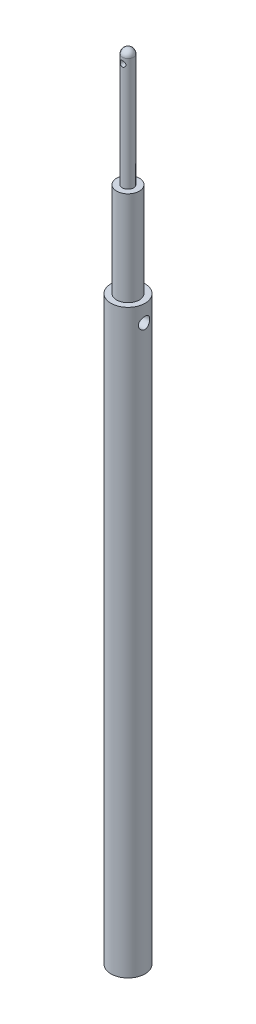
SolidWorks part; units mm, degrees
ref_plane "Front Plane" through (0, 0, 0) normal (0, 0, 1) x (1, 0, 0)
ref_plane "Top Plane" through (0, 0, 0) normal (0, 1, 0) x (1, 0, 0)
ref_plane "Right Plane" through (0, 0, 0) normal (1, 0, 0) x (0, 0, -1)
sketch "Sketch1" plane through (0, 0, 0) normal (0, 1, 0) x (1, 0, 0)
  circle A0 centre (0, 0) radius 9
  dimension "D1" = 18
extrude "Boss-Extrude1" add sketch "Sketch1" along normal blind 308
sketch "Sketch3" plane through (0, 0, 0) normal (1, 0, 0) x (0, 0, -1)
  line L1 (0, -1000) -> (0, 49000) construction
  line L2 (-1000, 299) -> (49000, 299) construction
  line L3 (9, 308) -> (-9, 308) construction
  circle A0 centre (0, 299) radius 3
  dimension "D1" = 6
  dimension "D2" = 9
extrude "Cut-Extrude1" cut sketch "Sketch3" against normal mid plane 200
sketch "Sketch4" plane through (0, 308, 0) normal (0, 1, 0) x (1, 0, 0)
  circle A0 centre (0, 0) radius 6
extrude "Boss-Extrude2" add sketch "Sketch4" along normal blind 50
sketch "Sketch5" plane through (0, 358, 0) normal (0, 1, 0) x (1, 0, 0)
  circle A0 centre (0, 0) radius 3
extrude "Boss-Extrude3" add sketch "Sketch5" along normal blind 60
sketch "Sketch8" plane through (0, 0, 0) normal (0, 0, 1) x (1, 0, 0)
  line L1 (3, 418) -> (-3, 418)
  arc A0 (3, 418) -> (-3, 418) centre (0, 418) ccw
revolve "Revolve1" add sketch "Sketch8" angle 360 about L1
sketch "Sketch6" plane through (0, 0, 0) normal (0, 0, 1) x (1, 0, 0)
  line L1 (3, 418) -> (-3, 418) construction
  circle A0 centre (0, 415) radius 1.5
  dimension "D2" = 3
  dimension "D1" = 3
extrude "Cut-Extrude4" cut sketch "Sketch6" against normal blind 40 and the other way blind 30 contours A0
